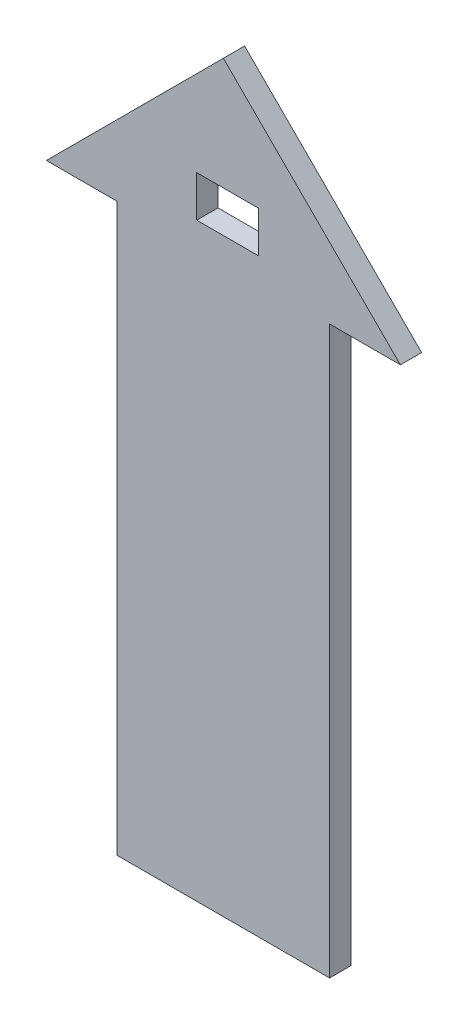
SolidWorks part; units mm, degrees
ref_plane "Front Plane" through (0, 0, 0) normal (0, 0, 1) x (1, 0, 0)
ref_plane "Top Plane" through (0, 0, 0) normal (0, 1, 0) x (1, 0, 0)
ref_plane "Right Plane" through (0, 0, 0) normal (1, 0, 0) x (0, 0, -1)
sketch "Model" plane through (0, 0, 0) normal (0, 0, 1) x (1, 0, 0)
  line L0 (0, 0) -> (30, 0)
  line L1 (30, 0) -> (30, 80)
  line L2 (30, 80) -> (40, 80)
  line L3 (40, 80) -> (15, 105)
  line L4 (0, 0) -> (0, 80)
  line L5 (0, 80) -> (-10, 80)
  line L6 (-10, 80) -> (15, 105)
extrude "Boss-Extrude2" add sketch "Model" along normal blind 3
sketch "Sketch2" plane through (0, 0, 3) normal (0, 0, 1) x (1, 0, 0)
  line L1 (11.2358, 89.1338) -> (19.9253, 89.1338)
  line L2 (11.2358, 89.1338) -> (11.2358, 83.3153)
  line L3 (11.2358, 83.3153) -> (19.9253, 83.3153)
  line L4 (19.9253, 89.1338) -> (19.9253, 83.3153)
extrude "Cut-Extrude1" cut sketch "Sketch2" against normal blind 3
